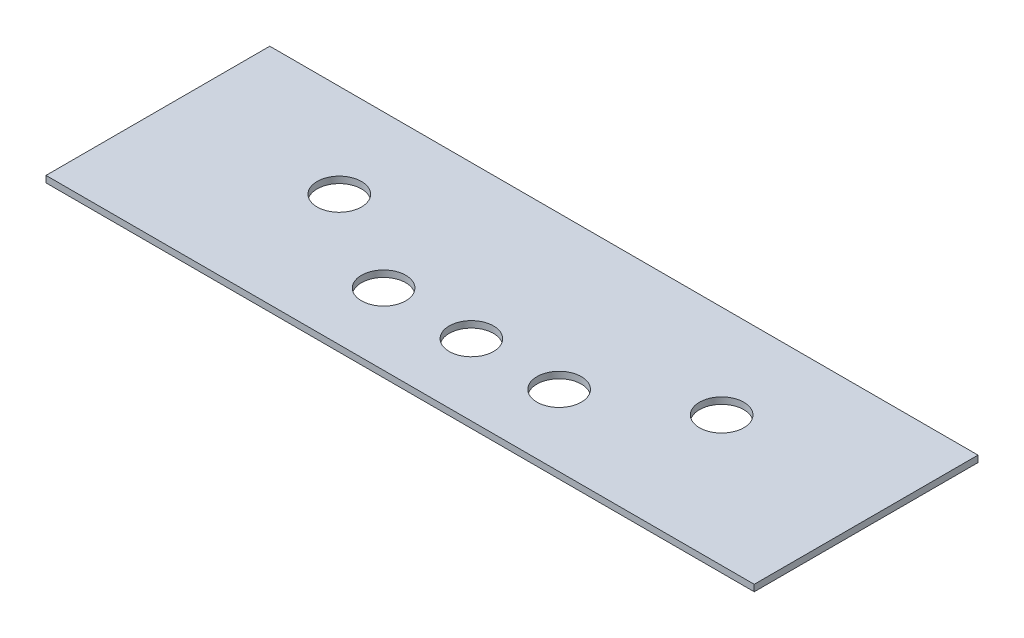
SolidWorks part; units mm, degrees
ref_plane "Front Plane" through (0, 0, 0) normal (0, 0, 1) x (1, 0, 0)
ref_plane "Top Plane" through (0, 0, 0) normal (0, 1, 0) x (1, 0, 0)
ref_plane "Right Plane" through (0, 0, 0) normal (1, 0, 0) x (0, 0, -1)
sketch "Sketch2" plane through (0, 0, 0) normal (0, 1, 0) x (1, 0, 0)
  line L1 (163, -51.5) -> (-163, -51.5)
  line L2 (163, -51.5) -> (163, 51.5)
  line L3 (163, 51.5) -> (-163, 51.5)
  line L4 (-163, -51.5) -> (-163, 51.5)
  line L5 (163, -51.5) -> (-163, 51.5) construction
  line L6 (163, 51.5) -> (-163, -51.5) construction
  point P0 (0, 0)
  dimension "D1" = 103
  dimension "D2" = 326
extrude "Boss-Extrude1" add sketch "Sketch2" along normal blind 3
sketch "Sketch3" plane through (0, 3, 0) normal (0, 1, 0) x (1, 0, 0)
  line L0 (163, 51.5) -> (-163, 51.5) construction
  line L1 (-163, 51.5) -> (-163, -51.5) construction
  line L2 (163, -51.5) -> (163, 51.5) construction
  circle A0 centre (-88, 8.5) radius 10.2
  circle A1 centre (88, 8.5) radius 10.2
  circle A2 centre (-40.4, -18.7) radius 10.2
  circle A3 centre (0, -18.7) radius 10.2
  circle A4 centre (40.4, -18.7) radius 10.2
  dimension "D1" = 43
  dimension "D2" = 43
  dimension "D3" = 75
  dimension "D4" = 20.4
  dimension "D5" = 75
  dimension "D6" = 20.4
  dimension "D7" = 20.4
  dimension "D8" = 20.4
  dimension "D9" = 20.4
  dimension "D10" = 60
  dimension "D11" = 60
  dimension "D12" = 60
  dimension "D13" = 20
  dimension "D14" = 20
extrude "Cut-Extrude1" cut sketch "Sketch3" along normal up to surface (3 mm away) from surface
